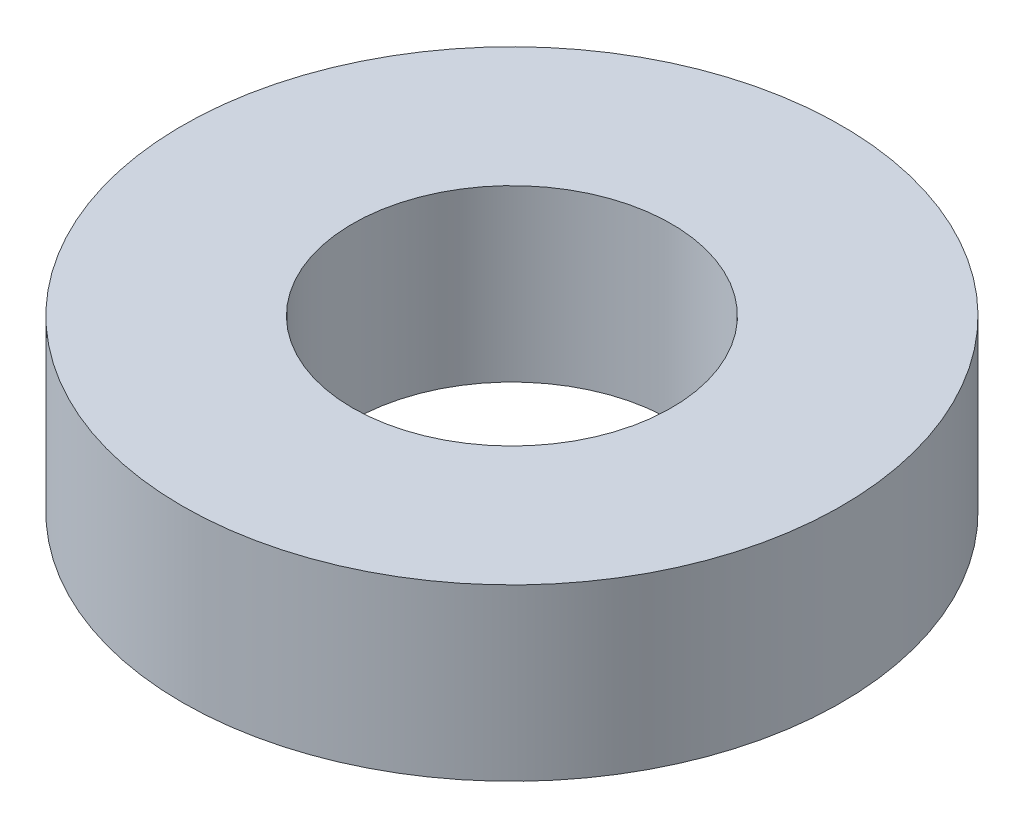
SolidWorks part; units mm, degrees
ref_plane "Front Plane" through (0, 0, 0) normal (0, 0, 1) x (1, 0, 0)
ref_plane "Top Plane" through (0, 0, 0) normal (0, 1, 0) x (1, 0, 0)
ref_plane "Right Plane" through (0, 0, 0) normal (1, 0, 0) x (0, 0, -1)
sketch "Sketch1" plane through (0, 0, 0) normal (0, 1, 0) x (1, 0, 0)
  circle A0 centre (0, 0) radius 15
  circle A1 centre (0, 0) radius 31
  dimension "D1" = 30
  dimension "D2" = 62
extrude "Boss-Extrude1" add sketch "Sketch1" along normal blind 16
